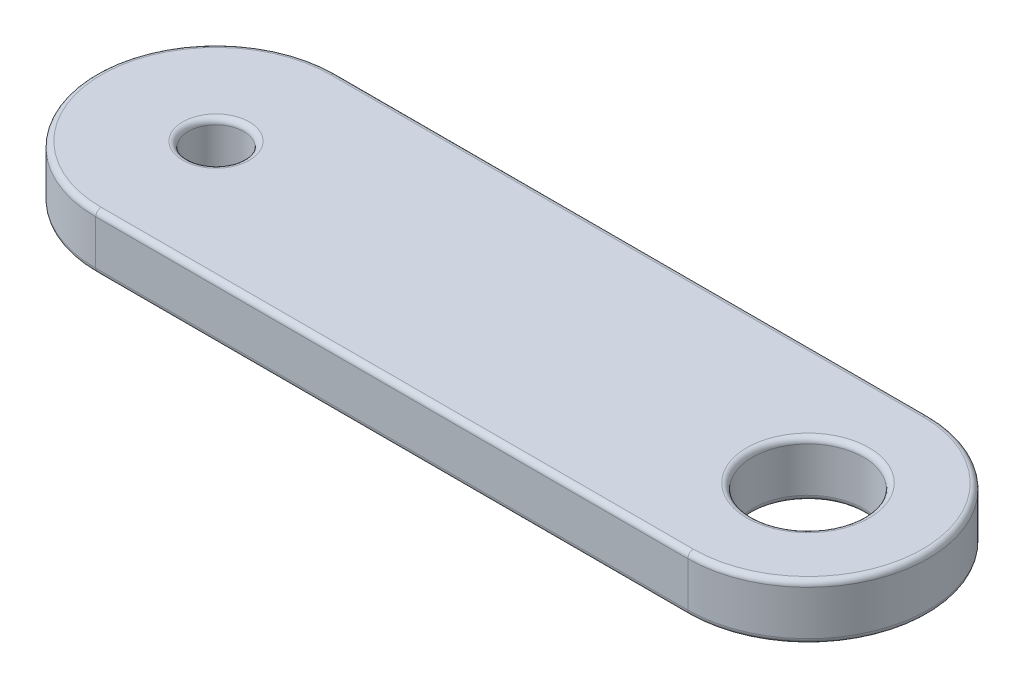
SolidWorks part; units mm, degrees
material "AISI 1020"
ref_plane "Front Plane" through (0, 0, 0) normal (0, 0, 1) x (1, 0, 0)
ref_plane "Top Plane" through (0, 0, 0) normal (0, 1, 0) x (1, 0, 0)
ref_plane "Right Plane" through (0, 0, 0) normal (1, 0, 0) x (0, 0, -1)
sketch "Sketch1" plane through (0, 0, 0) normal (0, 1, 0) x (1, 0, 0)
  line L0 (-8, 0) -> (8, 0) construction
  line L1 (-8, 3.25) -> (8, 3.25)
  line L2 (-8, -3.25) -> (8, -3.25)
  arc A0 (-8, 3.25) -> (-8, -3.25) centre (-8, 0) ccw
  arc A1 (8, -3.25) -> (8, 3.25) centre (8, 0) ccw
  circle A2 centre (-8, 0) radius 0.75
  circle A3 centre (8, 0) radius 1.5
  point P3 (0, 0)
  dimension "D1" = 1.5
  dimension "D3" = 6.5
  dimension "D4" = 3
  dimension "D2" = 16
extrude "Boss-Extrude1" add sketch "Sketch1" along normal mid plane 1.5
fillet "Fillet1" radius 0.15 12 edges at (8, -0.75, 1.5) (-8, -0.75, 0.75) (0, -0.75, 3.25) (11.25, -0.75, 0) (0, -0.75, -3.25) (-11.25, -0.75, 0) (8, 0.75, 1.5) (0, 0.75, -3.25) (11.25, 0.75, 0) (0, 0.75, 3.25) (-11.25, 0.75, 0) (-8, 0.75, 0.75)
